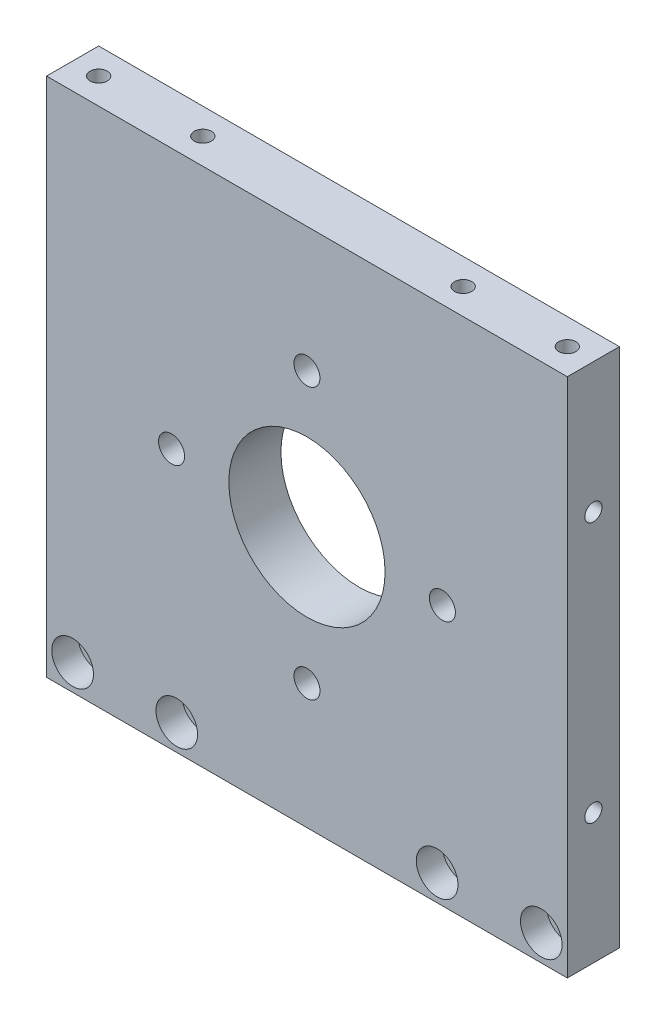
SolidWorks part; units mm, degrees
material "ALUMINIUM,  6082-T6"
ref_plane "Front Plane" through (0, 0, 0) normal (0, 0, 1) x (1, 0, 0)
ref_plane "Top Plane" through (0, 0, 0) normal (0, 1, 0) x (1, 0, 0)
ref_plane "Right Plane" through (0, 0, 0) normal (1, 0, 0) x (0, 0, -1)
sketch "Sketch1" plane through (0, 0, 0) normal (1, 0, 0) x (0, 0, -1)
  line L0 (-5, 50) -> (-5, -50)
  line L2 (-5, -50) -> (5, -50)
  line L8 (5, -50) -> (5, 50)
  line L9 (5, 50) -> (-5, 50)
  line L10 (-5, 50) -> (5, -50) construction
  dimension "D1" = 100
  dimension "D2" = 10
extrude "Boss-Extrude1" add sketch "Sketch1" along normal mid plane 100
sketch "Sketch2" plane through (0, 0, 5) normal (0, 0, 1) x (1, 0, 0)
  circle A0 centre (0, 0) radius 15
  dimension "D1" = 30
extrude "Cut-Extrude1" cut sketch "Sketch2" against normal blind 10
hole_wizard "CBORE for M4 Hex Socket Head Cap Screw1" positions "Sketch11" profile "Sketch12" counterbore size "M4" standard "ISO" end condition through all
sketch "Sketch11" plane through (0, 0, 5) normal (0, 0, 1) x (1, 0, 0)
  line L0 (-45, -45) -> (-25, -45) construction
  line L1 (-25, -45) -> (25, -45) construction
  line L2 (25, -45) -> (45, -45) construction
  line L4 (0, 0) -> (0, -45) construction
  line L6 (50, -50) -> (-50, -50) construction
  line L7 (-50, 50) -> (-50, -50) construction
  point P0 (-45, -45)
  point P2 (-25, -45)
  point P4 (25, -45)
  point P6 (45, -45)
  dimension "D1" = 5
  dimension "D2" = 5
  dimension "D3" = 20
sketch "Sketch12" plane through (-45, -45, 5) normal (1, 0, 0) x (0, -1, 0)
  line L0 (0, 0) -> (0, 10)
  line L1 (0, 10) -> (2.25, 10)
  line L3 (2.25, 10) -> (2.25, 5)
  line L4 (2.25, 5) -> (4, 5)
  line L5 (4, 5) -> (4, 0)
  line L7 (4, 0) -> (0, 0)
  line L11 (0, -6.35) -> (0, 107.95) construction
  dimension "Thru Hole Dia." = 4.5
  dimension "Thru Hole Depth" = 10
  dimension "C'Bore Dia." = 8
  dimension "C'Bore Depth" = 5
hole_wizard "M4 Tapped Hole1" positions "Sketch13" profile "Sketch14" tap size "M4" standard "ISO"
sketch "Sketch13" plane through (0, 50, 0) normal (0, 1, 0) x (1, 0, 0)
  line L0 (-45, 0) -> (-25, 0) construction
  line L1 (-25, 0) -> (25, 0) construction
  line L2 (25, 0) -> (45, 0) construction
  line L4 (-50, 5) -> (-50, -5) construction
  point P0 (-45, 0)
  point P2 (-25, 0)
  point P4 (25, 0)
  point P6 (45, 0)
  dimension "D1" = 20
  dimension "D2" = 5
sketch "Sketch14" plane through (-45, 50, 0) normal (1, 0, 0) x (0, 0, 1)
  line L0 (0, 0) -> (0, 11.9914)
  line L1 (0, 11.9914) -> (1.65, 11)
  line L2 (1.65, 11) -> (1.65, 0)
  line L5 (1.65, 0) -> (0, 0)
  line L10 (0, 11.9914) -> (-1.65, 11) construction
  line L11 (0, -6.35) -> (0, 107.95) construction
  dimension "Tap Drill Dia." = 3.3
  dimension "Tap Drill Depth" = 11
  dimension "Drill Angle" = 118
cosmetic thread "Hole Thread1" parameters "D1"=8, "D2"=4
cosmetic thread "Hole Thread2" parameters "D1"=8, "D2"=4
cosmetic thread "Hole Thread3" parameters "D1"=8, "D2"=4
cosmetic thread "Hole Thread4" parameters "D1"=8, "D2"=4
hole_wizard "M4 Tapped Hole2" positions "Sketch15" profile "Sketch16" tap size "M4" standard "ISO"
sketch "Sketch15" plane through (-50, 0, 0) normal (-1, 0, 0) x (0, 0, 1)
  line L0 (0, 25) -> (0, -25) construction
  point P0 (0, 25)
  point P2 (0, -25)
  dimension "D1" = 50
sketch "Sketch16" plane through (-50, 25, 0) normal (0, 1, 0) x (0, 0, 1)
  line L0 (0, 0) -> (0, 11.9914)
  line L1 (0, 11.9914) -> (1.65, 11)
  line L2 (1.65, 11) -> (1.65, 0)
  line L5 (1.65, 0) -> (0, 0)
  line L10 (0, 11.9914) -> (-1.65, 11) construction
  line L11 (0, -6.35) -> (0, 107.95) construction
  dimension "Tap Drill Dia." = 3.3
  dimension "Tap Drill Depth" = 11
  dimension "Drill Angle" = 118
cosmetic thread "Hole Thread5" parameters "D1"=8, "D2"=4
cosmetic thread "Hole Thread6" parameters "D1"=8, "D2"=4
hole_wizard "M4 Tapped Hole3" positions "Sketch17" profile "Sketch18" tap size "M4" standard "ISO"
sketch "Sketch17" plane through (50, 0, 0) normal (1, 0, 0) x (0, 0, -1)
  point P0 (0, 25)
  point P3 (0, -25)
sketch "Sketch18" plane through (50, 25, 0) normal (0, 1, 0) x (0, 0, -1)
  line L0 (0, 0) -> (0, 11.9914)
  line L1 (0, 11.9914) -> (1.65, 11)
  line L2 (1.65, 11) -> (1.65, 0)
  line L5 (1.65, 0) -> (0, 0)
  line L10 (0, 11.9914) -> (-1.65, 11) construction
  line L11 (0, -6.35) -> (0, 107.95) construction
  dimension "Tap Drill Dia." = 3.3
  dimension "Tap Drill Depth" = 11
  dimension "Drill Angle" = 118
cosmetic thread "Hole Thread7" parameters "D1"=8, "D2"=4
cosmetic thread "Hole Thread8" parameters "D1"=8, "D2"=4
hole_wizard "M6 Tapped Hole1" positions "Sketch19" profile "Sketch20" tap size "M6" standard "ISO" end condition through all
sketch "Sketch19" plane through (0, 0, 5) normal (0, 0, 1) x (1, 0, 0)
  circle A0 centre (0, 0) radius 26 construction
  point P0 (0, 26)
  point P3 (-26, 0)
  point P6 (26, 0)
  point P9 (0, -26)
  dimension "D1" = 52
sketch "Sketch20" plane through (0, 26, 5) normal (1, 0, 0) x (0, -1, 0)
  line L0 (0, 0) -> (0, 10)
  line L1 (0, 10) -> (2.5, 10)
  line L2 (2.5, 10) -> (2.5, 0)
  line L5 (2.5, 0) -> (0, 0)
  line L11 (0, -6.35) -> (0, 107.95) construction
  dimension "Thru Tap Drill Dia." = 5
  dimension "Thru Tap Drill Depth" = 10
cosmetic thread "Hole Thread9" parameters "D2"=6
cosmetic thread "Hole Thread10" parameters "D2"=6
cosmetic thread "Hole Thread11" parameters "D2"=6
cosmetic thread "Hole Thread12" parameters "D2"=6
